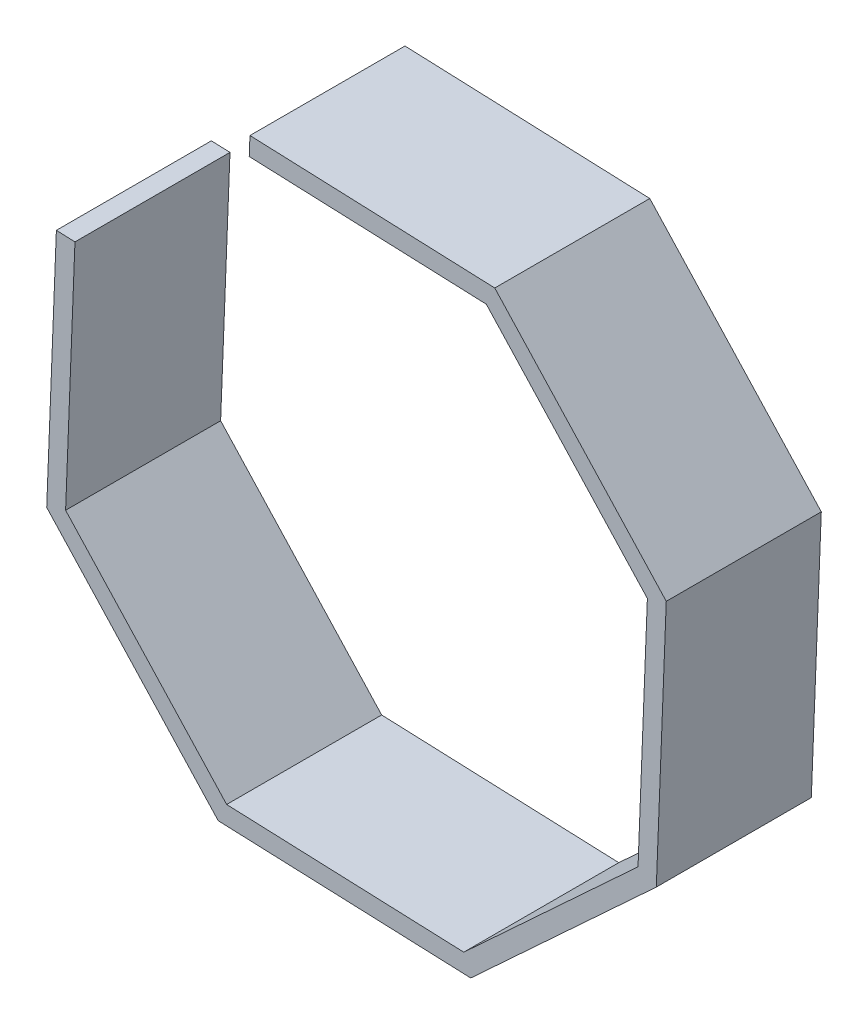
SolidWorks part; units mm, degrees
ref_plane "Front Plane" through (0, 0, 0) normal (0, 0, 1) x (1, 0, 0)
ref_plane "Top Plane" through (0, 0, 0) normal (0, 1, 0) x (1, 0, 0)
ref_plane "Right Plane" through (0, 0, 0) normal (1, 0, 0) x (0, 0, -1)
sketch "Sketch1" plane through (0, 0, 0) normal (0, 0, 1) x (1, 0, 0)
  line L11 (-45.4039, 20.9401) -> (0, 0) construction
  line L12 (20.9401, 45.4039) -> (-17.2985, 46.9123)
  line L14 (-45.4039, 20.9401) -> (-46.9123, -17.2985)
  line L15 (-46.9123, -17.2985) -> (-20.9401, -45.4039)
  line L16 (-20.9401, -45.4039) -> (17.2985, -46.9123)
  line L17 (17.2985, -46.9123) -> (45.4039, -20.9401)
  line L18 (45.4039, -20.9401) -> (46.9123, 17.2985)
  line L19 (46.9123, 17.2985) -> (20.9401, 45.4039)
  line L20 (-17.2985, 46.9123) -> (-45.4039, 20.9401) [skipped]
  line L21 (0, 0) -> (-17.2985, 46.9123) construction
  point P1 (0, 0)
extrude "Extrude-Thin3" add sketch "Sketch1" along normal blind 25 thin
